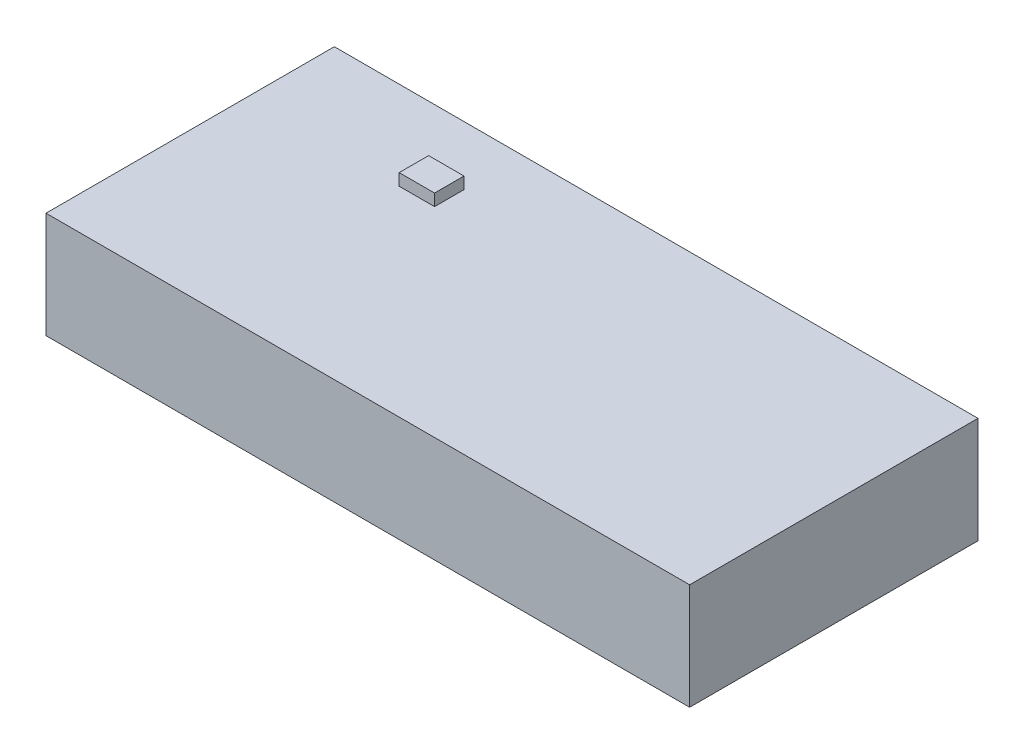
SolidWorks part; units mm, degrees
ref_plane "Front Plane" through (0, 0, 0) normal (0, 0, 1) x (1, 0, 0)
ref_plane "Top Plane" through (0, 0, 0) normal (0, 1, 0) x (1, 0, 0)
ref_plane "Right Plane" through (0, 0, 0) normal (1, 0, 0) x (0, 0, -1)
sketch "Sketch1" plane through (0, 0, 0) normal (0, 1, 0) x (1, 0, 0)
  line L1 (-69.342, 31.0642) -> (69.342, 31.0642)
  line L2 (-69.342, 31.0642) -> (-69.342, -31.0642)
  line L3 (-69.342, -31.0642) -> (69.342, -31.0642)
  line L4 (69.342, 31.0642) -> (69.342, -31.0642)
  line L5 (-69.342, 31.0642) -> (69.342, -31.0642) construction
  line L6 (-69.342, -31.0642) -> (69.342, 31.0642) construction
  point P0 (0, 0)
  dimension "D1" = 138.684
  dimension "D2" = 62.1284
extrude "Boss-Extrude1" add sketch "Sketch1" along normal mid plane 22.86
sketch "Sketch3" plane through (0, 0, -31.0642) normal (0, 0, -1) x (-1, 0, 0)
  line L0 (69.342, 11.43) -> (69.342, -11.43) construction
  line L1 (23.622, 3.175) -> (36.322, 3.175)
  line L2 (23.622, 3.175) -> (23.622, -3.175)
  line L3 (23.622, -3.175) -> (36.322, -3.175)
  line L4 (36.322, 3.175) -> (36.322, -3.175)
  line L5 (23.622, 3.175) -> (36.322, -3.175) construction
  line L6 (23.622, -3.175) -> (36.322, 3.175) construction
  line L7 (0, 0) -> (69.342, 0) construction
  line L8 (43.942, 3.175) -> (56.642, 3.175)
  line L9 (43.942, 3.175) -> (43.942, -3.175)
  line L10 (43.942, -3.175) -> (56.642, -3.175)
  line L11 (56.642, 3.175) -> (56.642, -3.175)
  line L12 (43.942, 3.175) -> (56.642, -3.175) construction
  line L13 (43.942, -3.175) -> (56.642, 3.175) construction
  line L14 (20.32, 0) -> (89.662, 0) construction
  point P0 (29.972, 0)
  point P12 (50.292, 0)
  dimension "D1" = 12.7
  dimension "D2" = 6.35
  dimension "D3" = 33.02
  dimension "D4" = 2
extrude "Cut-Extrude1" cut sketch "Sketch3" against normal blind 12.7
sketch "Sketch4" plane through (0, 11.43, 0) normal (0, 1, 0) x (1, 0, 0)
  line L0 (-69.342, 31.0642) -> (-69.342, -31.0642) construction
  line L1 (-36.322, 18.3642) -> (-28.702, 18.3642)
  line L2 (-36.322, 18.3642) -> (-36.322, 12.0142)
  line L3 (-36.322, 12.0142) -> (-28.702, 12.0142)
  line L4 (-28.702, 18.3642) -> (-28.702, 12.0142)
  line L5 (-36.322, 18.3642) -> (-28.702, 12.0142) construction
  line L6 (-36.322, 12.0142) -> (-28.702, 18.3642) construction
  line L7 (69.342, 31.0642) -> (-69.342, 31.0642) construction
  point P0 (-32.512, 15.1892)
  dimension "D1" = 7.62
  dimension "D2" = 6.35
  dimension "D3" = 33.02
  dimension "D4" = 12.7
extrude "Boss-Extrude2" add sketch "Sketch4" along normal blind 2.54
